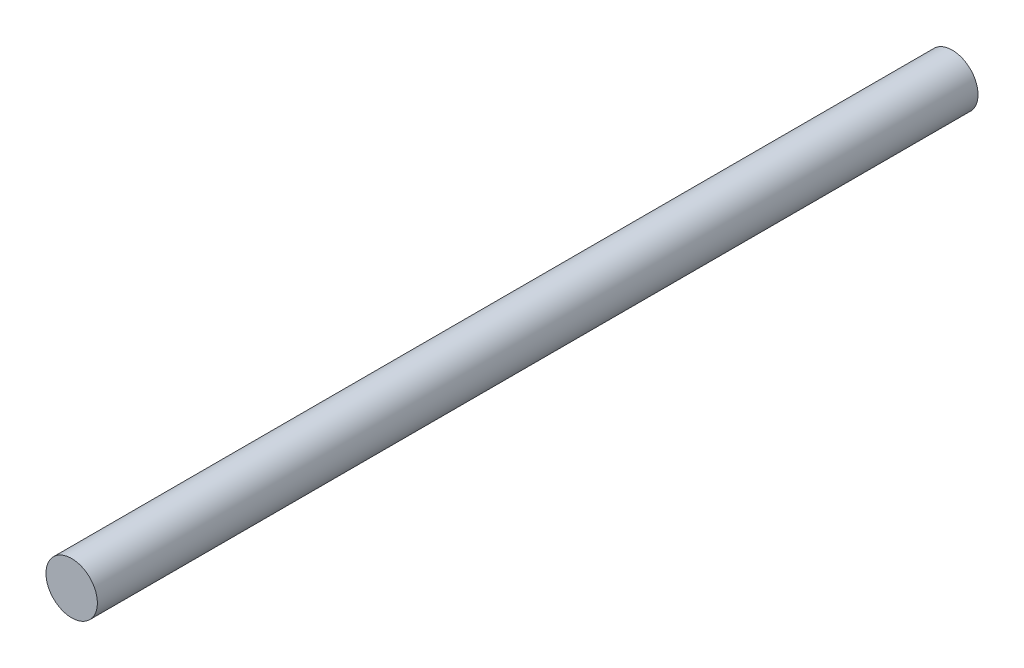
SolidWorks part; units mm, degrees
material "Plain Carbon Steel"
ref_plane "Front Plane" through (0, 0, 0) normal (0, 0, 1) x (1, 0, 0)
ref_plane "Top Plane" through (0, 0, 0) normal (0, 1, 0) x (1, 0, 0)
ref_plane "Right Plane" through (0, 0, 0) normal (1, 0, 0) x (0, 0, -1)
sketch "Sketch1" plane through (0, 0, 0) normal (0, 0, 1) x (1, 0, 0)
  circle A0 centre (0, 0) radius 7.9375
  dimension "D1" = 15.875
extrude "Extrude1" add sketch "Sketch1" along normal mid plane 271.78
